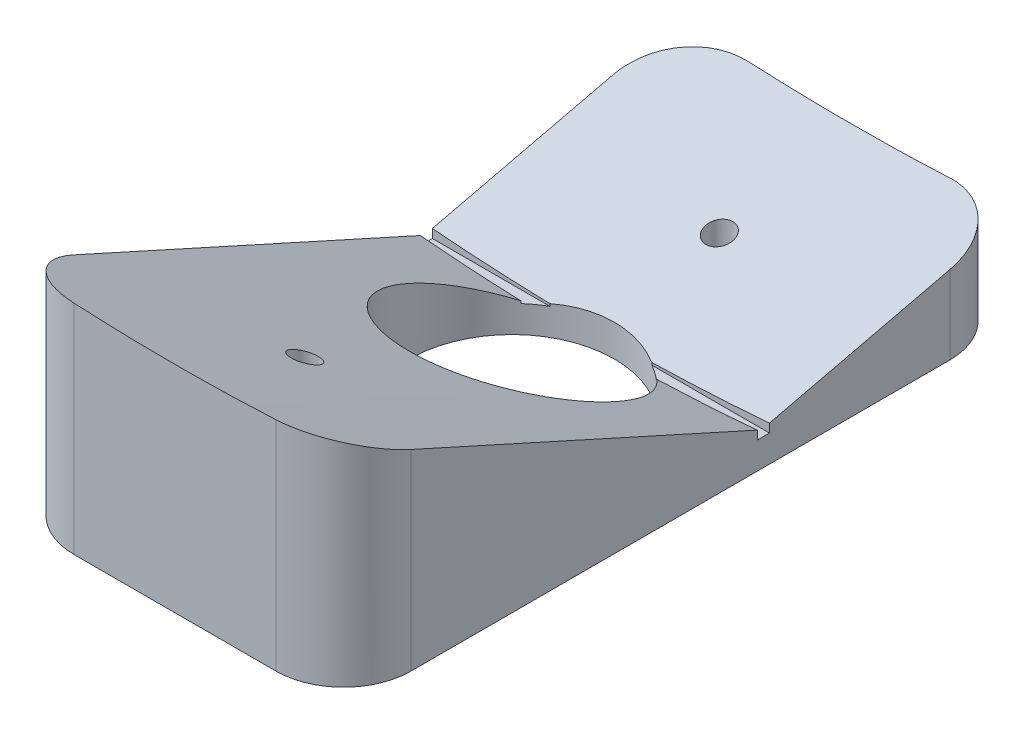
SolidWorks part; units mm, degrees
ref_plane "Front Plane" through (0, 0, 0) normal (0, 0, 1) x (1, 0, 0)
ref_plane "Top Plane" through (0, 0, 0) normal (0, 1, 0) x (1, 0, 0)
ref_plane "Right Plane" through (0, 0, 0) normal (1, 0, 0) x (0, 0, -1)
sketch "Sketch1" plane through (0, 0, 0) normal (0, 1, 0) x (1, 0, 0)
  line L0 (0, -30.75) -> (0, 30.75) construction
  line L1 (0, -30.75) -> (0, -50) construction
  line L2 (-25, 50) -> (25, 50)
  line L3 (-25, 50) -> (-25, -50)
  line L4 (-25, -50) -> (25, -50)
  line L5 (25, 50) -> (25, -50)
  line L6 (0, 0) -> (25, 0) construction
  circle A0 centre (0, 0) radius 15.2
  circle A1 centre (0, 30.75) radius 2
  circle A2 centre (0, -30.75) radius 2
  point P0 (0, -30.75)
  point P1 (0, 30.75)
  dimension "D2" = 30.4
  dimension "D3" = 4
  dimension "D1" = 61.5
  dimension "D4" = 50
  dimension "D5" = 100
extrude "Boss-Extrude1" add sketch "Sketch1" along normal blind 33
sketch "Sketch2" plane through (25, 0, 0) normal (1, 0, 0) x (0, 0, -1)
  line L0 (50, 14) -> (12, 5)
  line L1 (50, 33) -> (50, 0) construction
  line L2 (12, 5) -> (-50, 33)
  line L3 (50, 14) -> (50, 33)
  line L4 (50, 33) -> (-50, 33)
  line L5 (-50, 0) -> (50, 0) construction
  dimension "D1" = 5
  dimension "D2" = 14
  dimension "D3" = 38
extrude "Cut-Extrude1" cut sketch "Sketch2" against normal through all
chamfer "Chamfer1" distance 2.5 angle 45 2 edges at (0, 0, -28.75) (0, 0, 32.75)
ref_plane "Plane1" through (0, 24.3457, 53.9084) normal (0, -0.4116, -0.9114) x (-1, 0, 0)
sketch "Sketch3" plane through (0, 24.3457, 53.9084) normal (0, -0.4116, -0.9114) x (-1, 0, 0)
  line L0 (25, 9.4959) -> (-25, 9.4959) construction
  line L1 (25, 9.4959) -> (-25, 9.4959)
  line L2 (0, 8.4959) -> (-25, 8.4959) construction
  line L3 (-25, 9.4959) -> (-25, 8.4959) construction
  arc A0 (25, 9.4959) -> (-25, 9.4959) centre (0, 321.4959) cw
  dimension "D1" = 1
extrude "Cut-Extrude2" cut sketch "Sketch3" along normal up to vertex (68.0294 mm away)
ref_plane "Plane2" through (0, 11.9567, -50.4839) normal (0, 0.2305, -0.9731) x (-1, 0, 0)
sketch "Sketch4" plane through (0, 11.9567, -50.4839) normal (0, 0.2305, -0.9731) x (-1, 0, 0)
  line L0 (25, 2.0998) -> (-25, 2.0998) construction
  line L1 (25, 2.0998) -> (-25, 2.0998)
  line L2 (-25, 2.0998) -> (-25, 1.0998) construction
  line L3 (-25, 2.0998) -> (-25, -11.5233) construction
  line L4 (-25, 1.0998) -> (0, 1.0998) construction
  arc A0 (-25, 2.0998) -> (25, 2.0998) centre (0, 314.0998) ccw
  dimension "D1" = 1
extrude "Cut-Extrude4" cut sketch "Sketch4" against normal up to vertex (39.0512 mm away)
sketch "Sketch6" plane through (-25, 0, 0) normal (-1, 0, 0) x (0, 0, 1)
  line L0 (50, 33) -> (-12, 5) construction
  line L1 (-13.1808, 4) -> (-11.3808, 4)
  line L2 (-13.1808, 4) -> (-13.1808, 5.2797)
  line L3 (-13.1808, 5.2797) -> (-11.3808, 5.2797)
  line L4 (-11.3808, 4) -> (-11.3808, 5.2797)
  line L5 (-12, 5) -> (-50, 14) construction
  line L6 (-50, 0) -> (50, 0) construction
  dimension "D1" = 4
  dimension "D2" = 1.8
extrude "Cut-Extrude5" cut sketch "Sketch6" against normal through all
fillet "Fillet1" radius 10 4 edges at (25, 16.5, 50) (25, 7, -50) (-25, 7, -50) (-25, 16.5, 50)
sketch "Sketch7" plane through (0, 0, 0) normal (0, -1, 0) x (1, 0, 0)
  line L0 (0, -42.5) -> (0, 42.5) construction
  point P0 (0, 42.5)
  point P1 (0, -42.5)
  point P4 (0, 0)
  dimension "D1" = 85
hole_wizard "Ø4.5 (4.5) Diameter Hole1" positions "Sketch7" profile "Sketch8" hole size "Ø4.5" standard "ISO"
sketch "Sketch8" plane through (0, 0, 42.5) normal (1, 0, 0) x (0, 0, -1)
  line L0 (0, 0) -> (0, 9.3519)
  line L1 (0, 9.3519) -> (2.25, 8)
  line L2 (2.25, 8) -> (2.25, 0)
  line L5 (2.25, 0) -> (0, 0)
  line L10 (0, 9.3519) -> (-2.25, 8) construction
  line L11 (0, -6.35) -> (0, 107.95) construction
  dimension "Hole Dia." = 4.5
  dimension "Hole Depth" = 8
  dimension "Drill Angle" = 118
